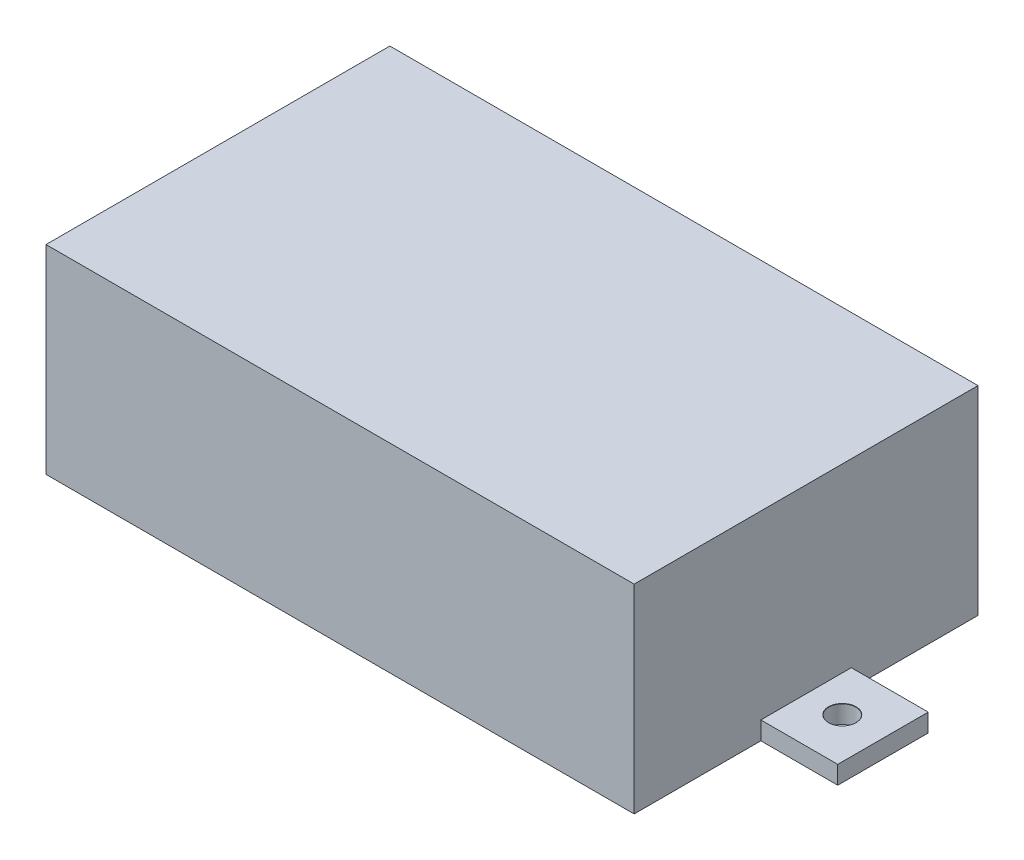
SolidWorks part; units mm, degrees
ref_plane "Front Plane" through (0, 0, 0) normal (0, 0, 1) x (1, 0, 0)
ref_plane "Top Plane" through (0, 0, 0) normal (0, 1, 0) x (1, 0, 0)
ref_plane "Right Plane" through (0, 0, 0) normal (1, 0, 0) x (0, 0, -1)
sketch "Sketch1" plane through (0, 0, 0) normal (0, 1, 0) x (1, 0, 0)
  line L1 (-32.5, 19) -> (32.5, 19)
  line L2 (-32.5, 19) -> (-32.5, -19)
  line L3 (-32.5, -19) -> (32.5, -19)
  line L4 (32.5, 19) -> (32.5, -19)
  line L5 (-32.5, 19) -> (32.5, -19) construction
  line L6 (-32.5, -19) -> (32.5, 19) construction
  point P0 (0, 0)
  dimension "D1" = 65
  dimension "D2" = 38
extrude "Boss-Extrude1" add sketch "Sketch1" along normal blind 22
sketch "Sketch2" plane through (0, 0, 0) normal (0, -1, 0) x (1, 0, 0)
  line L1 (-41, 5) -> (41, 5)
  line L2 (-41, 5) -> (-41, -5)
  line L3 (-41, -5) -> (41, -5)
  line L4 (41, 5) -> (41, -5)
  line L5 (-41, 5) -> (41, -5) construction
  line L6 (-41, -5) -> (41, 5) construction
  point P0 (0, 0)
  dimension "D1" = 10
  dimension "D2" = 82
extrude "Boss-Extrude2" add sketch "Sketch2" against normal blind 2
hole_wizard "Ø3.0 (3) Diameter Hole1" positions "Sketch3" profile "Sketch4" hole size "Ø3.0" standard "ISO" end condition through all
sketch "Sketch3" plane through (0, 2, 0) normal (0, 1, 0) x (1, 0, 0)
  line L0 (-36.5, 0) -> (36.5, 0) construction
  point P0 (-36.5, 0)
  point P3 (36.5, 0)
  dimension "D1" = 73
sketch "Sketch4" plane through (-36.5, 2, 0) normal (1, 0, 0) x (0, 0, 1)
  line L0 (0, 0) -> (0, 2)
  line L1 (0, 2) -> (1.5, 2)
  line L2 (1.5, 2) -> (1.5, 0.025)
  line L3 (1.5, 0.025) -> (1.525, 0)
  line L5 (1.525, 0) -> (0, 0)
  line L6 (-1.5, 0.025) -> (-1.525, 0) construction
  line L11 (0, -6.35) -> (0, 107.95) construction
  dimension "Thru Hole Dia." = 3
  dimension "Thru Hole Depth" = 2
  dimension "Near C'Sink Dia." = 3.05
  dimension "Near C'Sink Angle" = 90
